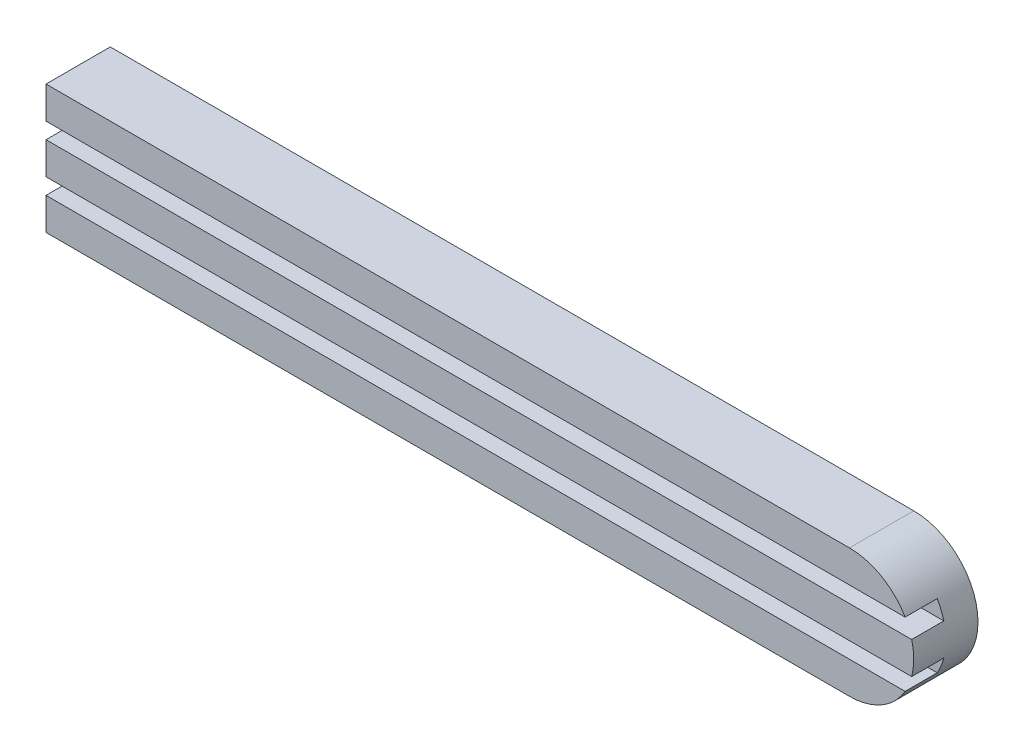
SolidWorks part; units mm, degrees
ref_plane "Front Plane" through (0, 0, 0) normal (0, 0, 1) x (1, 0, 0)
ref_plane "Top Plane" through (0, 0, 0) normal (0, 1, 0) x (1, 0, 0)
ref_plane "Right Plane" through (0, 0, 0) normal (1, 0, 0) x (0, 0, -1)
sketch "Sketch2" plane through (0, 0, 0) normal (0, 0, 1) x (1, 0, 0)
  line L0 (0, 0) -> (250, 0)
  line L1 (0, 0) -> (0, 40)
  line L2 (0, 40) -> (250, 40)
  arc A0 (250, 40) -> (250, 0) centre (250, 20) cw
  dimension "D1" = 40
  dimension "D2" = 250
extrude "Boss-Extrude1" add sketch "Sketch2" along normal blind 10
sketch "Sketch3" plane through (0, 0, 10) normal (0, 0, 1) x (1, 0, 0)
  line L0 (250, 40) -> (0, 40)
  line L1 (0, 40) -> (0, 30)
  line L2 (0, 0) -> (250, 0)
  line L3 (0, 30) -> (267.3205, 30)
  line L4 (0, 25) -> (269.3649, 25)
  line L5 (0, 10) -> (115.0439, 10)
  line L6 (0, 15) -> (269.3649, 15)
  line L7 (0, 25) -> (0, 0)
  line L8 (267.3205, 10) -> (115.0439, 10)
  arc A0 (250, 0) -> (267.3205, 10) centre (250, 20) ccw
  arc A1 (267.3205, 30) -> (250, 40) centre (250, 20) ccw
  arc A2 (269.3649, 15) -> (269.3649, 25) centre (250, 20) ccw
  line M7 (0, 40) -> (0, 0)
  line M8 (0, 0) -> (250, 0)
  arc M9 (250, 0) -> (250, 40) centre (250, 20) ccw
  line M10 (250, 40) -> (0, 40)
  dimension "D1" = 10
  dimension "D2" = 5
  dimension "D3" = 10
  dimension "D4" = 5
extrude "Boss-Extrude2" add sketch "Sketch3" along normal blind 10 contours L8 L5 M9 M7 M8 | L6 L4 M7 M9 | L3 M7 M9 M10
